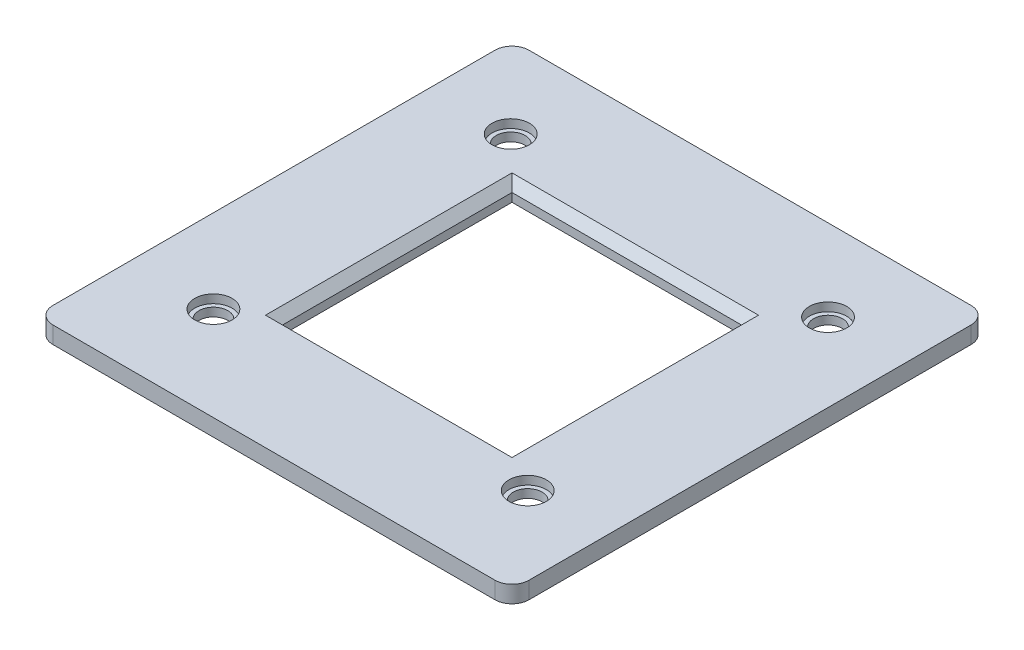
SolidWorks part; units mm, degrees
ref_plane "Front Plane" through (0, 0, 0) normal (0, 0, 1) x (1, 0, 0)
ref_plane "Top Plane" through (0, 0, 0) normal (0, 1, 0) x (1, 0, 0)
ref_plane "Right Plane" through (0, 0, 0) normal (1, 0, 0) x (0, 0, -1)
sketch "Sketch1" plane through (0, 0, 0) normal (0, 1, 0) x (1, 0, 0)
  line L1 (0, 0) -> (56, 0)
  line L2 (0, 0) -> (0, 56)
  line L3 (0, 56) -> (56, 56)
  line L4 (56, 0) -> (56, 56)
  line L5 (14.5, 14.5) -> (41.5, 14.5)
  line L6 (14.5, 14.5) -> (14.5, 41.5)
  line L7 (14.5, 41.5) -> (41.5, 41.5)
  line L8 (41.5, 14.5) -> (41.5, 41.5)
  point P9 (28, 41.5)
  point P10 (28, 56)
  point P11 (41.5, 28)
  point P12 (56, 28)
  dimension "D1" = 56
  dimension "D2" = 56
  dimension "D3" = 27
  dimension "D4" = 27
  dimension "D5" = 0
  dimension "D6" = 0
extrude "Boss-Extrude1" add sketch "Sketch1" along normal blind 2
chamfer "Chamfer1" distance 1 angle 45 4 edges at (41.5, 2, -28) (28, 2, -14.5) (14.5, 2, -28) (28, 2, -41.5)
hole_wizard "CBORE for M3 Cross Recess Pan Head Screw1" positions "Sketch8" profile "Sketch7" counterbore size "M3" standard "IS"
sketch "Sketch8" plane through (0, 2, 0) normal (0, 1, 0) x (1, 0, 0)
  point P0 (9.4619, 46.3843)
  point P2 (46.7945, 46.3843)
  point P4 (46.7945, 11.0516)
  point P6 (9.8209, 11.0516)
sketch "Sketch7" plane through (9.4619, 2, -46.3843) normal (1, 0, 0) x (0, 0, 1)
  line L0 (0, 0) -> (0, 6.0215)
  line L1 (0, 6.0215) -> (1.7, 5)
  line L2 (1.7, 5) -> (1.7, 1)
  line L3 (1.7, 1) -> (2.2, 1)
  line L4 (2.2, 1) -> (2.2, 0)
  line L5 (2.2, 0) -> (0, 0)
  line L10 (0, 6.0215) -> (-1.7, 5) construction
  line L11 (0, -6.35) -> (0, 107.95) construction
  dimension "Hole Dia." = 3.4
  dimension "Hole Depth" = 5
  dimension "C'Bore Dia." = 4.4
  dimension "C'Bore Depth" = 1
  dimension "Drill Angle" = 118
fillet "Fillet1" radius 2 4 edges at (56, 1, -56) (0, 1, -56) (56, 1, 0) (0, 1, 0)
